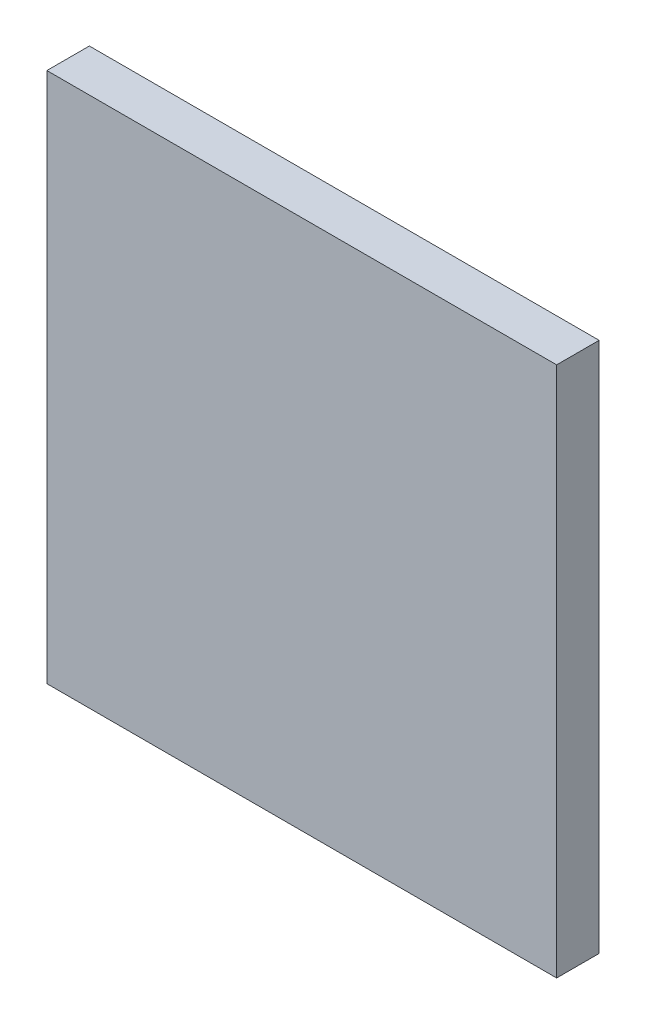
SolidWorks part; units mm, degrees
ref_plane "Top Plane" through (0, 0, 0) normal (0, 0, 1) x (1, 0, 0)
ref_plane "Front Plane" through (0, 0, 0) normal (0, 1, 0) x (1, 0, 0)
ref_plane "Right Plane" through (0, 0, 0) normal (1, 0, 0) x (0, 0, -1)
sketch "Sketch1" plane through (0, 0, 0) normal (0, 0, 1) x (1, 0, 0)
  line L1 (0, 0) -> (12, 0)
  line L2 (0, 0) -> (0, 12.5)
  line L3 (0, 12.5) -> (12, 12.5)
  line L4 (12, 0) -> (12, 12.5)
  dimension "D1" = 12
  dimension "D2" = 12.5
extrude "Boss-Extrude1" add sketch "Sketch1" along normal blind 1
sketch "Sketch2" plane through (0, 0, 0) normal (0, 0, 1) x (1, 0, 0)
  line L0 (1.5, 1.5) -> (1.5, 11)
  line L1 (1.5, 11) -> (10.5, 11)
  line L2 (10.5, 11) -> (10.5, 1.5)
  line L3 (10.5, 1.5) -> (3, 1.5)
  line L4 (1.5, 11) -> (1.5, 12.5) construction
  line L5 (12, 12.5) -> (0, 12.5) construction
  line L6 (1.5, 11) -> (0, 11) construction
  line L7 (0, 12.5) -> (0, 0) construction
  line L8 (1.5, 1.5) -> (0, 1.5) construction
  line L9 (1.5, 1.5) -> (1.5, 0) construction
  line L10 (0, 0) -> (12, 0) construction
  line L11 (10.5, 12.5) -> (10.5, 11) construction
  line L12 (10.5, 1.5) -> (12, 1.5) construction
  line L13 (12, 0) -> (12, 12.5) construction
  line L14 (10.5, 1.5) -> (10.5, 0) construction
  line L15 (10.5, 11) -> (12, 11) construction
  line L16 (3, 1.5) -> (1.5, 1.5) construction
  line L17 (3, 1.5) -> (3, 9.5)
  line L18 (3, 9.5) -> (9, 9.5)
  line L19 (9, 9.5) -> (9, 3)
  line L20 (9, 3) -> (4.5, 3)
  line L21 (3, 11) -> (3, 9.5) construction
  line L22 (1.5, 9.5) -> (3, 9.5) construction
  line L23 (9, 11) -> (9, 9.5) construction
  line L24 (10.5, 9.5) -> (9, 9.5) construction
  line L25 (9, 3) -> (9, 1.5) construction
  line L26 (10.5, 3) -> (9, 3) construction
  line L27 (4.5, 3) -> (4.5, 1.5) construction
  line L28 (4.5, 3) -> (3, 3) construction
  line L29 (-4.5, 1.5) -> (0, 1.5) construction
  line L30 (-4.5, 1.5) -> (-4.5, 11) construction
  line L31 (1.5, 17) -> (10.5, 17) construction
  line L32 (16.5, 11) -> (16.5, 1.5) construction
  line L33 (-3, 1.5) -> (-3, 9.5) construction
  line L34 (10.5, -4.5) -> (3, -4.5) construction
  line L35 (3, 15.5) -> (9, 15.5) construction
  line L36 (15, 9.5) -> (15, 3) construction
  line L37 (9, -3) -> (4.5, -3) construction
  line L38 (0, 0) -> (-4.5, 0) construction
  line L39 (-4.5, 0) -> (-4.5, 1.5) construction
  circle A1 centre (-4.5, 1.5) radius 6 construction
  arc A2 (-4.5, 11) -> (1.5, 17) centre (1.5, 11) cw construction
  arc A3 (10.5, 17) -> (16.5, 11) centre (10.5, 11) cw construction
  arc A4 (16.5, 1.5) -> (10.5, -4.5) centre (10.5, 1.5) cw construction
  arc A5 (3, -4.5) -> (-3, 1.5) centre (3, 1.5) cw construction
  arc A6 (-3, 9.5) -> (3, 15.5) centre (3, 9.5) cw construction
  arc A7 (9, 15.5) -> (15, 9.5) centre (9, 9.5) cw construction
  arc A8 (15, 3) -> (9, -3) centre (9, 3) cw construction
  arc A9 (4.5, -3) -> (-1.5, 3) centre (4.5, 3) cw construction
  circle A11 centre (1.5, 17) radius 6 construction
  point P62 (1.945, 16.9699)
  point P63 (1.5, 16.0846)
  dimension "D1" = 1.5
  dimension "D2" = 12
  dimension "D3" = 1.5
  dimension "D4" = 6
  dimension "D5" = 6
  dimension "D6" = 1.5
  dimension "D7" = 11
  dimension "D8" = 12.5
  dimension "D9" = 12
